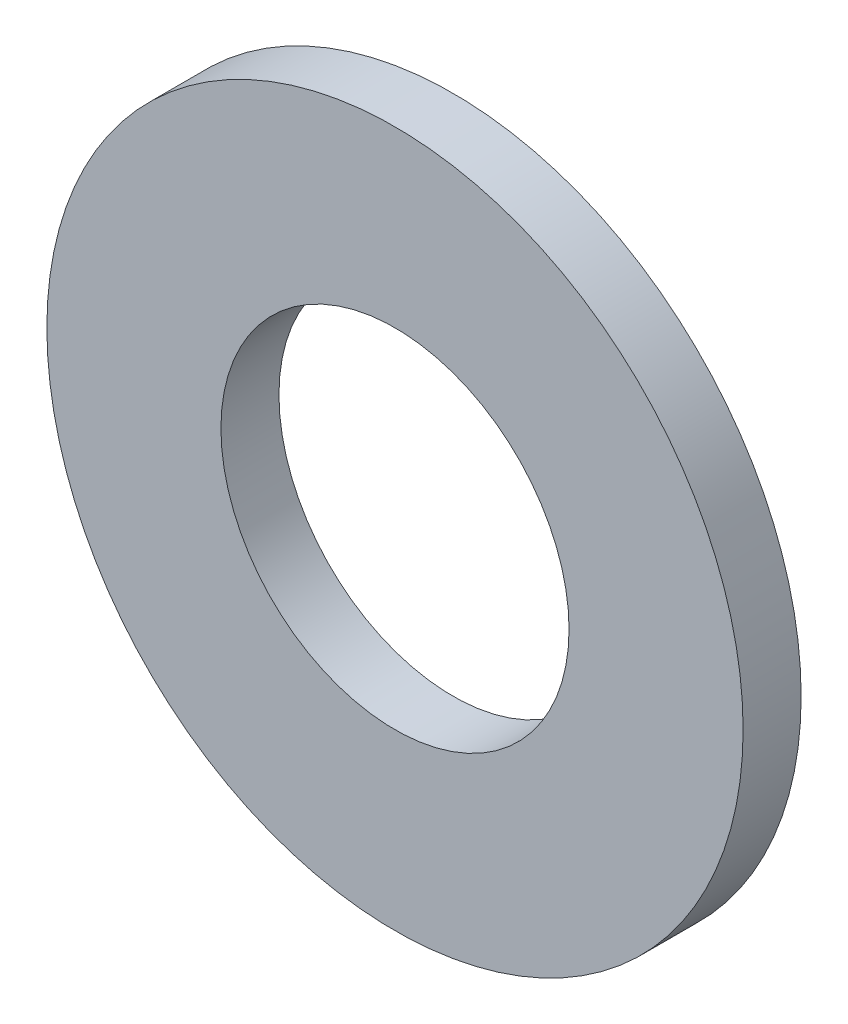
SolidWorks part; units mm, degrees
ref_plane "Front Plane" through (0, 0, 0) normal (0, 0, 1) x (1, 0, 0)
ref_plane "Top Plane" through (0, 0, 0) normal (0, 1, 0) x (1, 0, 0)
ref_plane "Right Plane" through (0, 0, 0) normal (1, 0, 0) x (0, 0, -1)
sketch "Sketch1" plane through (0, 0, 0) normal (0, 0, 1) x (1, 0, 0)
  circle A0 centre (0, 0) radius 9.525
  circle A1 centre (0, 0) radius 4.7625
  dimension "D1" = 19.05
  dimension "ID" = 9.525
extrude "Extrude1" add sketch "Sketch1" along normal mid plane 1.5875
sketch "Sketch2" plane through (0, 0, 0) normal (1, 0, 0) x (0, 0, -1)
  line L0 (-0.7937, -4.7625) -> (0.7937, -4.7625) construction
  line L3 (0.7937, 4.7625) -> (-0.7937, 4.7625) construction
  line L5 (-0.7937, -4.7625) -> (0.7937, -4.7625)
  line L6 (0.7937, 4.7625) -> (-0.7937, 4.7625)
sketch "Sketch4" plane through (0, 0, 0.7937) normal (0, 0, 1) x (1, 0, 0)
  line L0 (0, 0) -> (-3.3676, 3.3676)
  line L1 (0, -0.8731) -> (0, 0.8731) construction
  circle A0 centre (0, 0) radius 4.7625 construction
  dimension "D1" = 45
